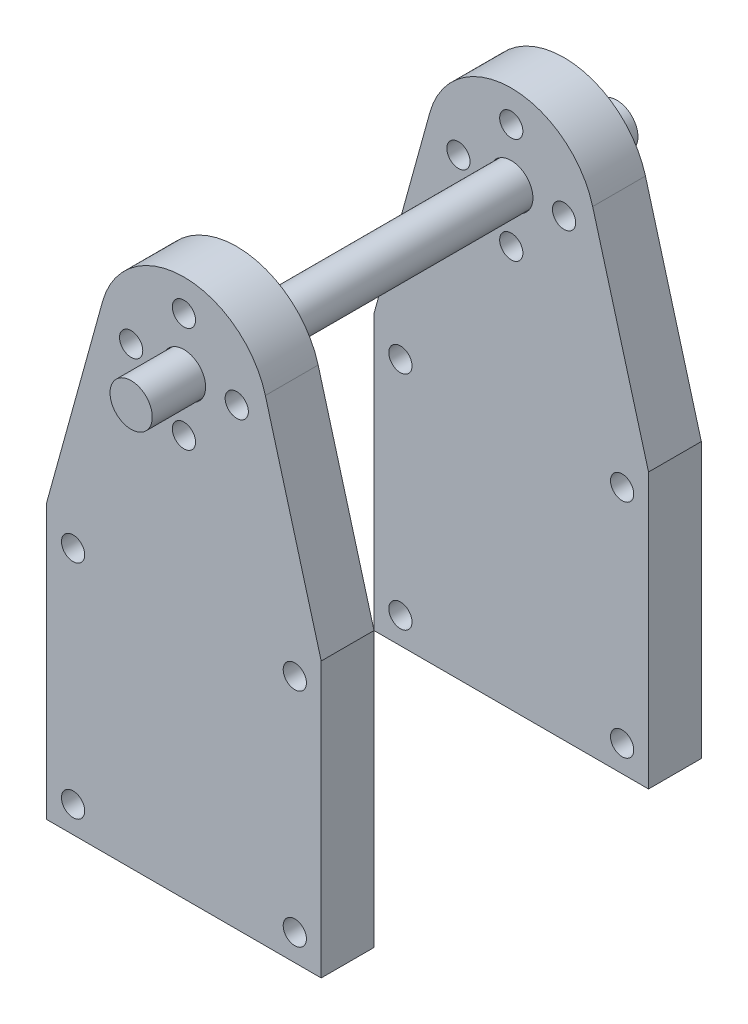
SolidWorks part; units mm, degrees
material "ABS"
ref_plane "正面" through (0, 0, 0) normal (0, 0, 1) x (1, 0, 0)
ref_plane "平面" through (0, 0, 0) normal (0, 1, 0) x (1, 0, 0)
ref_plane "右側面" through (0, 0, 0) normal (1, 0, 0) x (0, 0, -1)
sketch "ｽｹｯﾁ1" plane through (0, 0, 0) normal (0, 0, 1) x (1, 0, 0)
  line L1 (-10.5, 10.5) -> (10.5, 10.5) construction
  line L2 (-10.5, 10.5) -> (-10.5, -10.5) construction
  line L3 (-10.5, -10.5) -> (10.5, -10.5) construction
  line L4 (10.5, 10.5) -> (10.5, -10.5) construction
  line L5 (-10.5, 10.5) -> (10.5, -10.5) construction
  line L6 (-10.5, -10.5) -> (10.5, 10.5) construction
  line L7 (-13, -13) -> (13, -13)
  line L8 (13, -13) -> (13, 13)
  line L9 (-13, -13) -> (-13, 13)
  line L11 (0, 0) -> (0, 57.4086) construction
  line L12 (-13, 13) -> (-7.7107, 32.1317)
  line L13 (7.7107, 32.1317) -> (13, 13)
  circle A0 centre (-10.5, 10.5) radius 1.1
  circle A1 centre (10.5, 10.5) radius 1.1
  circle A2 centre (10.5, -10.5) radius 1.1
  circle A3 centre (-10.5, -10.5) radius 1.1
  arc A5 (7.7107, 32.1317) -> (-7.7107, 32.1317) centre (0, 30) ccw
  circle A6 centre (0, 30) radius 2.05
  circle A7 centre (0, 30) radius 5 construction
  circle A8 centre (0, 35) radius 1.1
  circle A9 centre (5, 30) radius 1.1
  circle A10 centre (0, 25) radius 1.1
  circle A11 centre (-5, 30) radius 1.1
  point P0 (0, 0)
  point P23 (-6.3607, 33.5774)
  point P24 (0, 0)
  point P25 (-13, 14.285)
  point P32 (0, 30)
  point P33 (0, 0)
  dimension "D6" = 2.2
  dimension "D7" = 16
  dimension "D8" = 4.1
  dimension "D9" = 10
  dimension "D10" = 2.2
  dimension "D1" = 21
  dimension "D2" = 21
  dimension "D3" = 13
  dimension "D4" = 13
  dimension "D5" = 13
  dimension "D12" = 13
  dimension "D13" = 30
  dimension "D11" = 4
extrude "ﾎﾞｽ - 押し出し1" add sketch "ｽｹｯﾁ1" along normal blind 5
ref_plane "平面1" through (0, 0, -26) normal (0, 0, 1) x (1, 0, 0)
sketch "ｽｹｯﾁ4" plane through (0, 0, -26) normal (0, 0, 1) x (1, 0, 0)
  line L5 (-13, 13) -> (-13, -13)
  line L6 (-7.7107, 32.1317) -> (-13, 13)
  line L7 (13, 13) -> (7.7107, 32.1317)
  line L8 (13, -13) -> (13, 13)
  line L9 (-13, -13) -> (13, -13)
  line L10 (-13, 13) -> (-13, -13)
  line L11 (-7.7107, 32.1317) -> (-13, 13)
  line L12 (13, 13) -> (7.7107, 32.1317)
  line L13 (13, -13) -> (13, 13)
  line L14 (-13, -13) -> (13, -13)
  circle A1 centre (-10.5, 10.5) radius 1.1
  circle A2 centre (-10.5, 10.5) radius 1.1
  circle A3 centre (10.5, 10.5) radius 1.1
  circle A4 centre (10.5, 10.5) radius 1.1
  circle A5 centre (10.5, -10.5) radius 1.1
  circle A6 centre (10.5, -10.5) radius 1.1
  circle A7 centre (-10.5, -10.5) radius 1.1
  circle A8 centre (-10.5, -10.5) radius 1.1
  circle A9 centre (0, 30) radius 2.05
  circle A10 centre (0, 30) radius 2.05
  circle A11 centre (0, 35) radius 1.1
  circle A12 centre (0, 35) radius 1.1
  circle A13 centre (5, 30) radius 1.1
  circle A14 centre (5, 30) radius 1.1
  circle A15 centre (0, 25) radius 1.1
  circle A16 centre (0, 25) radius 1.1
  circle A17 centre (-5, 30) radius 1.1
  circle A18 centre (-5, 30) radius 1.1
  arc A19 (7.7107, 32.1317) -> (-7.7107, 32.1317) centre (0, 30) ccw
  arc A20 (7.7107, 32.1317) -> (-7.7107, 32.1317) centre (0, 30) ccw
  dimension "D1" = 0
  dimension "D2" = 0
  dimension "D3" = 0
  dimension "D4" = 0
  dimension "D5" = 0
  dimension "D6" = 0
  dimension "D7" = 0
  dimension "D8" = 0
  dimension "D9" = 0
  dimension "D10" = 0
extrude "ﾎﾞｽ - 押し出し2" add sketch "ｽｹｯﾁ4" against normal blind 5 separate body
sketch "ｽｹｯﾁ6" plane through (0, 0, -31) normal (0, 0, -1) x (-1, 0, 0)
  circle A0 centre (0, 30) radius 2
  dimension "D1" = 4
extrude "ﾎﾞｽ - 押し出し3" add sketch "ｽｹｯﾁ6" against normal blind 41 and the other way blind 5 separate body
